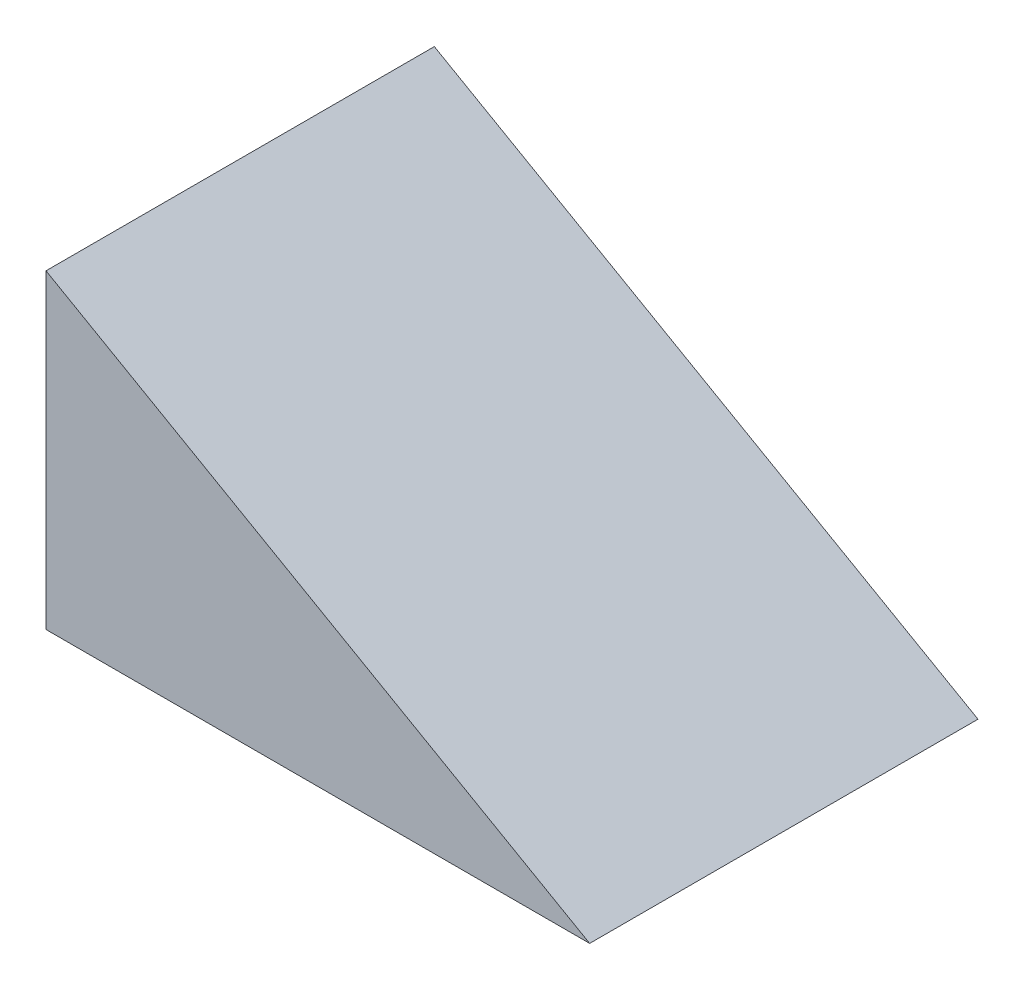
SolidWorks part; units mm, degrees
ref_plane "Front Plane" through (0, 0, 0) normal (0, 0, 1) x (1, 0, 0)
ref_plane "Top Plane" through (0, 0, 0) normal (0, 1, 0) x (1, 0, 0)
ref_plane "Right Plane" through (0, 0, 0) normal (1, 0, 0) x (0, 0, -1)
sketch "Sketch1" plane through (0, 0, 0) normal (0, 0, 1) x (1, 0, 0)
  line L0 (0, 0) -> (0, 40)
  line L1 (0, 40) -> (70, 0)
  line L2 (70, 0) -> (0, 0)
  dimension "D1" = 40
  dimension "D2" = 70
extrude "Boss-Extrude1" add sketch "Sketch1" along normal blind 50
